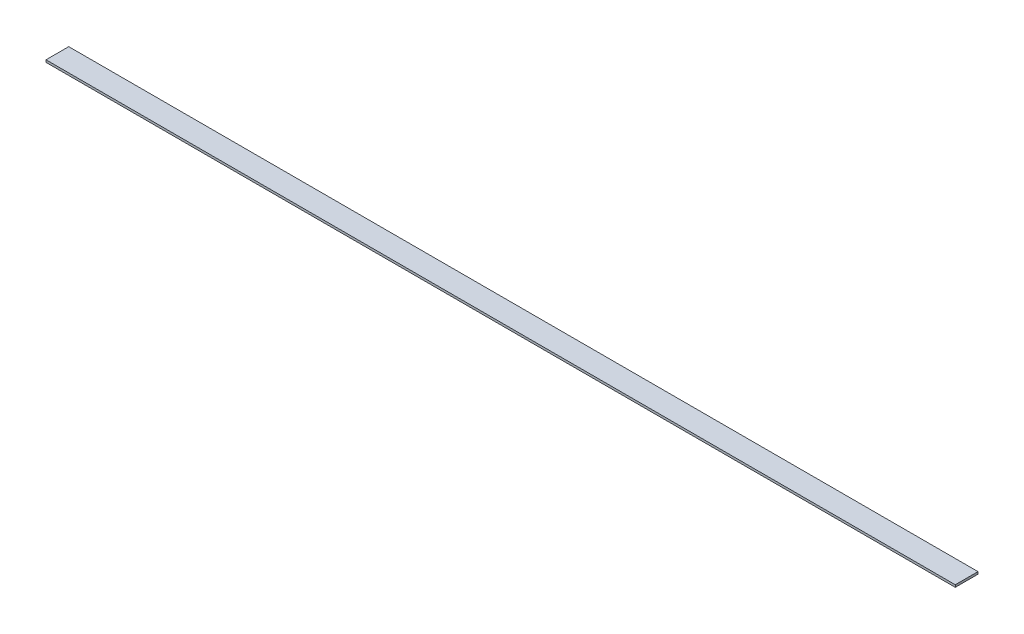
SolidWorks part; units mm, degrees
ref_plane "Front Plane" through (0, 0, 0) normal (0, 0, 1) x (1, 0, 0)
ref_plane "Top Plane" through (0, 0, 0) normal (0, 1, 0) x (1, 0, 0)
ref_plane "Right Plane" through (0, 0, 0) normal (1, 0, 0) x (0, 0, -1)
sketch "Sketch1" plane through (0, 0, 0) normal (0, 1, 0) x (1, 0, 0)
  line L1 (-119.5294, 8.5241) -> (-17.9294, 8.5241)
  line L2 (-119.5294, 8.5241) -> (-119.5294, 5.9841)
  line L3 (-119.5294, 5.9841) -> (-17.9294, 5.9841)
  line L4 (-17.9294, 8.5241) -> (-17.9294, 5.9841)
  dimension "D1" = 101.6
  dimension "D2" = 2.54
extrude "Boss-Extrude1" add sketch "Sketch1" along normal blind 0.254
